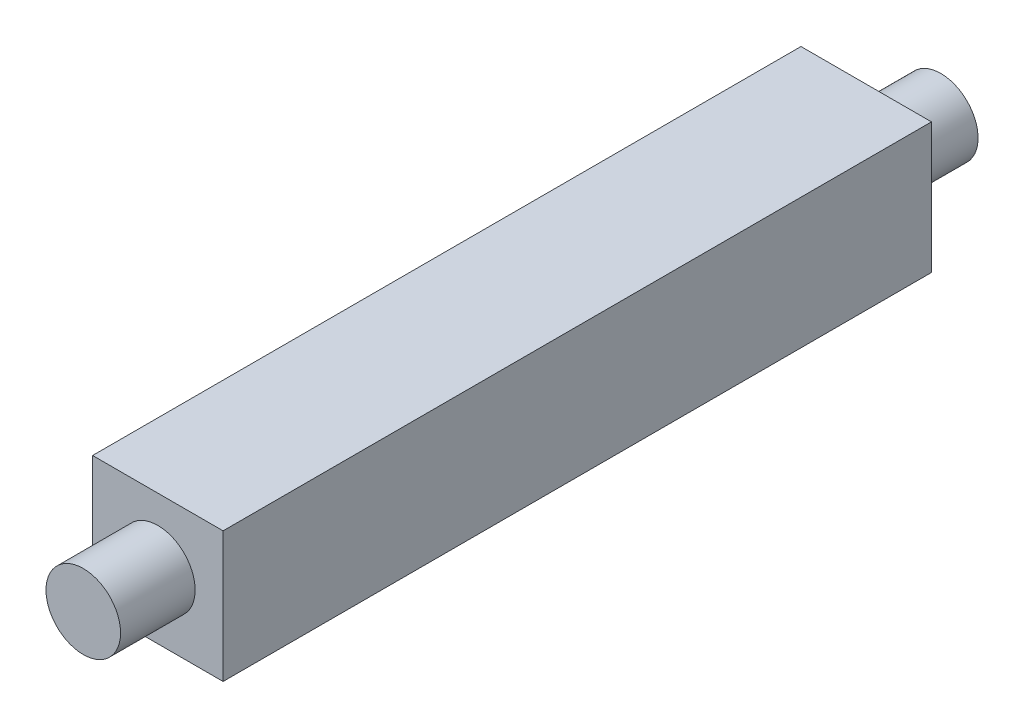
SolidWorks part; units mm, degrees
ref_plane "Front" through (0, 0, 0) normal (0, 0, 1) x (1, 0, 0)
ref_plane "Top" through (0, 0, 0) normal (0, 1, 0) x (1, 0, 0)
ref_plane "Right" through (0, 0, 0) normal (1, 0, 0) x (0, 0, -1)
sketch "Croquis1" plane through (0, 0, 0) normal (0, 0, 1) x (1, 0, 0)
  line L1 (-1.75, -1.75) -> (1.75, -1.75)
  line L2 (-1.75, -1.75) -> (-1.75, 1.75)
  line L3 (-1.75, 1.75) -> (1.75, 1.75)
  line L4 (1.75, -1.75) -> (1.75, 1.75)
  line L5 (-1.75, -1.75) -> (1.75, 1.75) construction
  line L6 (-1.75, 1.75) -> (1.75, -1.75) construction
  point P0 (0, 0)
  dimension "D1" = 3.5
  dimension "D2" = 3.5
extrude "Saliente-Extruir1" add sketch "Croquis1" along normal blind 19
sketch "Croquis2" plane through (0, 0, 19) normal (0, 0, 1) x (1, 0, 0)
  line L0 (1.75, 1.75) -> (-1.75, -1.75) construction
  line L1 (-1.75, 1.75) -> (1.75, -1.75) construction
  circle A0 centre (0, 0) radius 1
  dimension "D1" = 2
extrude "Saliente-Extruir2" add sketch "Croquis2" along normal blind 2
sketch "Croquis3" plane through (0, 0, 0) normal (0, 0, -1) x (-1, 0, 0)
  line L0 (1.75, 1.75) -> (-1.75, -1.75) construction
  line L1 (-1.75, 1.75) -> (1.75, -1.75) construction
  circle A0 centre (0, 0) radius 1
  dimension "D1" = 2
extrude "Saliente-Extruir3" add sketch "Croquis3" along normal blind 2
